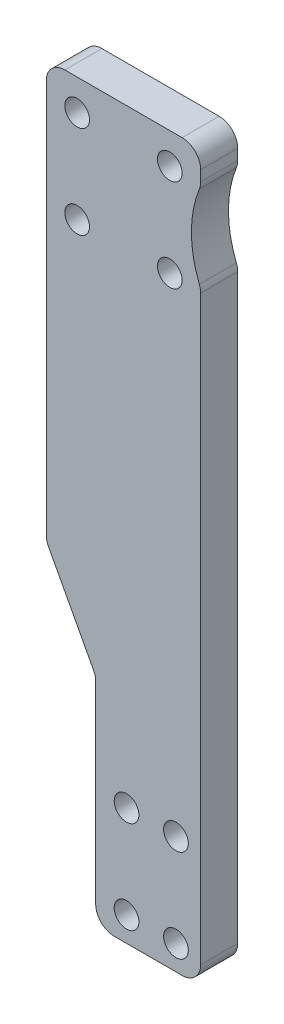
SolidWorks part; units mm, degrees
material "Thornel Mat VMA"
ref_plane "前视基准面" through (0, 0, 0) normal (0, 0, 1) x (1, 0, 0)
ref_plane "上视基准面" through (0, 0, 0) normal (0, 1, 0) x (1, 0, 0)
ref_plane "右视基准面" through (0, 0, 0) normal (1, 0, 0) x (0, 0, -1)
other "Configuration Table"
sketch "草图1" plane through (0, 0, 0) normal (0, 0, 1) x (1, 0, 0)
  line L0 (-10.5, 15) -> (-7, 87.5)
  line L1 (-12.5, -15) -> (12.5, -15)
  line L2 (-12.5, -15) -> (-12.5, 15)
  line L3 (-12.5, 15) -> (12.5, 15)
  line L4 (12.5, -15) -> (12.5, 15)
  line L5 (-12.5, -15) -> (12.5, 15)
  line L6 (-12.5, 15) -> (12.5, -15)
  line L7 (-7, 112.5) -> (18, 112.5)
  line L8 (-7, 112.5) -> (-7, 87.5)
  line L9 (-7, 87.5) -> (18, 87.5)
  line L10 (18, 112.5) -> (18, 87.5)
  line L11 (-7, 112.5) -> (18, 87.5)
  line L12 (-7, 87.5) -> (18, 112.5)
  line L17 (0, 0) -> (3.5, 0) construction
  line L19 (-2, 92.5) -> (13, 92.5) construction
  line L20 (-2, 92.5) -> (-2, 107.5) construction
  line L21 (-2, 107.5) -> (13, 107.5) construction
  line L22 (13, 92.5) -> (13, 107.5) construction
  line L23 (-2, 92.5) -> (13, 107.5) construction
  line L24 (-2, 107.5) -> (13, 92.5) construction
  line L25 (18, 87.5) -> (12.5, 15)
  line L27 (-0.5, -6) -> (7.5, -6) construction
  line L28 (-0.5, -6) -> (-0.5, 6) construction
  line L29 (-0.5, 6) -> (7.5, 6) construction
  line L30 (7.5, -6) -> (7.5, 6) construction
  line L31 (-0.5, -6) -> (7.5, 6) construction
  line L32 (-0.5, 6) -> (7.5, -6) construction
  circle A0 centre (13, 92.5) radius 2
  circle A1 centre (13, 107.5) radius 2
  circle A3 centre (-2, 107.5) radius 2
  circle A4 centre (-2, 92.5) radius 2
  circle A10 centre (7.5, 6) radius 2
  circle A11 centre (7.5, -6) radius 2
  circle A12 centre (-0.5, -6) radius 2
  circle A13 centre (-0.5, 6) radius 2
  point P6 (5.5, 100)
  point P16 (5.5, 100)
  dimension "D6" = 4
  dimension "D7" = 8
  dimension "D10" = 4
  dimension "D1" = 30
  dimension "D2" = 15
  dimension "D3" = 25
  dimension "D4" = 97.5
  dimension "D5" = 19.5
  dimension "D8" = 12
  dimension "D9" = 25
  dimension "D11" = 5
  dimension "D12" = 2
extrude "凸台-拉伸1" add sketch "草图1" along normal blind 6
sketch "草图2" plane through (0, 0, 6) normal (0, 0, 1) x (1, 0, 0)
  line L0 (5.5, 100) -> (34.5, 100) construction
  line L1 (13, 92.5) -> (-2, 107.5) construction
  circle A0 centre (34.5, 100) radius 18
  dimension "D2" = 36
  dimension "D1" = 29
extrude "切除-拉伸1" cut sketch "草图2" against normal blind 6
sketch "草图3" plane through (0, 0, 6) normal (0, 0, 1) x (1, 0, 0)
  line L0 (12.5, -15) -> (12.5, 15) construction
  line L1 (-10.5, 15) -> (-12.5, 15)
  line L2 (-10.5, 15) -> (-10.5, -15)
  line L3 (-10.5, -15) -> (-12.5, -15)
  line L4 (-12.5, 15) -> (-12.5, -15)
  line L5 (-12.5, -15) -> (12.5, -15)
  line L6 (-12.5, -15) -> (-12.5, -5)
  line L7 (-12.5, -5) -> (12.5, -5)
  line L8 (12.5, -15) -> (12.5, -5)
  line M9 (-12.5, -15) -> (12.5, -15)
  line M10 (12.5, -15) -> (12.5, 15)
  circle M13 centre (7.5, -6) radius 2
  circle M20 centre (-0.5, -6) radius 2
  dimension "D1" = 10
extrude "切除-拉伸2" cut sketch "草图3" against normal blind 10 contours L7 L2 M9 M10 M13 M20
sketch "草图4" plane through (0, 0, 6) normal (0, 0, 1) x (1, 0, 0)
  line L0 (-7, 103.074) -> (-7, -8.4388)
  line L1 (-7, 112.5) -> (-7, 87.5) construction
  line L13 (9.2321, -5) -> (12.5, -5)
  line L14 (12.5, -5) -> (12.5, 15)
  line L15 (12.5, 15) -> (18, 87.5)
  line L16 (18, 87.5) -> (18, 92.8063)
  line L17 (18, 107.1937) -> (18, 112.5)
  line L18 (18, 112.5) -> (-7, 112.5)
  line L19 (-7, 112.5) -> (-7, 87.5)
  line L20 (-7, 87.5) -> (-10.5, 15)
  line L21 (-10.5, 15) -> (-10.5, -5)
  line L22 (-10.5, -5) -> (-2.2321, -5)
  line L23 (1.2321, -5) -> (5.7679, -5)
  line L24 (9.2321, -5) -> (12.5, -5)
  line L25 (12.5, -5) -> (12.5, 15)
  line L26 (12.5, 15) -> (18, 87.5)
  line L27 (18, 87.5) -> (18, 92.8063)
  line L28 (18, 107.1937) -> (18, 112.5)
  line L29 (18, 112.5) -> (-7, 112.5)
  line L30 (-7, 112.5) -> (-7, 87.5)
  line L31 (-7, 87.5) -> (-10.5, 15)
  line L32 (-10.5, 15) -> (-10.5, -5)
  line L33 (-10.5, -5) -> (-2.2321, -5)
  line L34 (1.2321, -5) -> (5.7679, -5)
  arc A3 (9.2321, -5) -> (5.7679, -5) centre (7.5, -6) ccw
  arc A4 (18, 107.1937) -> (18, 92.8063) centre (34.5, 100) ccw
  arc A5 (1.2321, -5) -> (-2.2321, -5) centre (-0.5, -6) ccw
  arc A6 (9.2321, -5) -> (5.7679, -5) centre (7.5, -6) ccw
  arc A7 (18, 107.1937) -> (18, 92.8063) centre (34.5, 100) ccw
  arc A8 (1.2321, -5) -> (-2.2321, -5) centre (-0.5, -6) ccw
  line M31 (-7, 87.5) -> (-10.5, 15)
  line M32 (-10.5, 15) -> (-10.5, -5)
  line M33 (-10.5, -5) -> (-2.2321, -5)
  dimension "D1" = 0
extrude "切除-拉伸3" cut sketch "草图4" against normal blind 10 contours L0 M31 M32 M33
sketch "草图5" plane through (0, 0, 6) normal (0, 0, 1) x (1, 0, 0)
  line L0 (18, 87.5) -> (18, -5)
  line L1 (18, -5) -> (12.5, -5)
  line L2 (12.5, -5) -> (12.5, 15)
  line L3 (12.5, 15) -> (18, 87.5)
extrude "凸台-拉伸2" add sketch "草图5" against normal blind 6
sketch "草图6" plane through (0, 0, 6) normal (0, 0, 1) x (1, 0, 0)
  line L0 (9.2321, -5) -> (18, -5) construction
  line L1 (-4.0585, 9.4073) -> (11.7117, 9.4073)
  line L2 (-4.0585, 9.4073) -> (-4.0585, -5)
  line L3 (-4.0585, -5) -> (11.7117, -5)
  line L4 (11.7117, 9.4073) -> (11.7117, -5)
extrude "凸台-拉伸3" add sketch "草图6" against normal up to surface (6 mm away) up to face at (15, 107.5, 0)
sketch "草图7" plane through (0, 0, 6) normal (0, 0, 1) x (1, 0, 0)
  line L1 (-7, -5) -> (18, -5) construction
  line L2 (18, 92.8063) -> (18, -5) construction
  line L3 (-2, -1) -> (6, -1) construction
  line L4 (-2, -1) -> (-2, 14) construction
  line L5 (-2, 14) -> (6, 14) construction
  line L6 (6, -1) -> (6, 14) construction
  line L7 (-2, -1) -> (6, 14) construction
  line L8 (-2, 14) -> (6, -1) construction
  circle A0 centre (6, -1) radius 2
  circle A1 centre (6, 14) radius 2
  circle A2 centre (-2, 14) radius 2
  circle A3 centre (-2, -1) radius 2
  dimension "D4" = 4
  dimension "D1" = 8
  dimension "D2" = 15
  dimension "D3" = 4
  dimension "D5" = 12
extrude "切除-拉伸4" cut sketch "草图7" against normal blind 10
fillet "圆角1" radius 3 5 edges at (-7, 112.5, 3) (18, 107.1937, 3) (18, -5, 3) (-7, -5, 3) (18, 112.5, 3)
sketch "草图8" plane through (0, 0, 6) normal (0, 0, 1) x (1, 0, 0)
  line L0 (6, -1) -> (6, 14) construction
  line L1 (6, 14) -> (14, 14) construction
  line L2 (14, 14) -> (14, -1) construction
  line L3 (14, -1) -> (6, -1) construction
  circle A0 centre (14, 14) radius 2
  circle A1 centre (14, -1) radius 2
  circle A2 centre (6, 14) radius 2 construction
  dimension "D1" = 8
extrude "切除-拉伸5" cut sketch "草图8" against normal blind 10
sketch "草图9" plane through (0, 0, 6) normal (0, 0, 1) x (1, 0, 0)
  line L0 (-7, 109.5) -> (-7, -2) construction
  line L1 (-7, 30) -> (1, 30)
  line L2 (-7, 30) -> (-7, -5)
  line L3 (-7, -5) -> (1, -5)
  line L4 (1, 30) -> (1, -5)
  line L5 (-4, -5) -> (15, -5) construction
  circle A0 centre (6, 14) radius 2 construction
  dimension "D1" = 5
  dimension "D2" = 35
extrude "切除-拉伸6" cut sketch "草图9" against normal blind 10
sketch "草图10" plane through (0, 0, 6) normal (0, 0, 1) x (1, 0, 0)
  line L0 (1, 30) -> (-7, 30)
  line L1 (-7, 30) -> (-7, 45)
  line L2 (-7, 109.5) -> (-7, 30) construction
  line L3 (-7, 45) -> (1, 30)
  dimension "D1" = 15
extrude "切除-拉伸7" cut sketch "草图10" against normal blind 10
fillet "圆角2" radius 3 3 edges at (1, -5, 3) (1, 30, 3) (-7, 45, 3)
chamfer "倒角2" distance 2 angle 45 2 edges at (0, 92.5, 0) (0, 107.5, 0)
